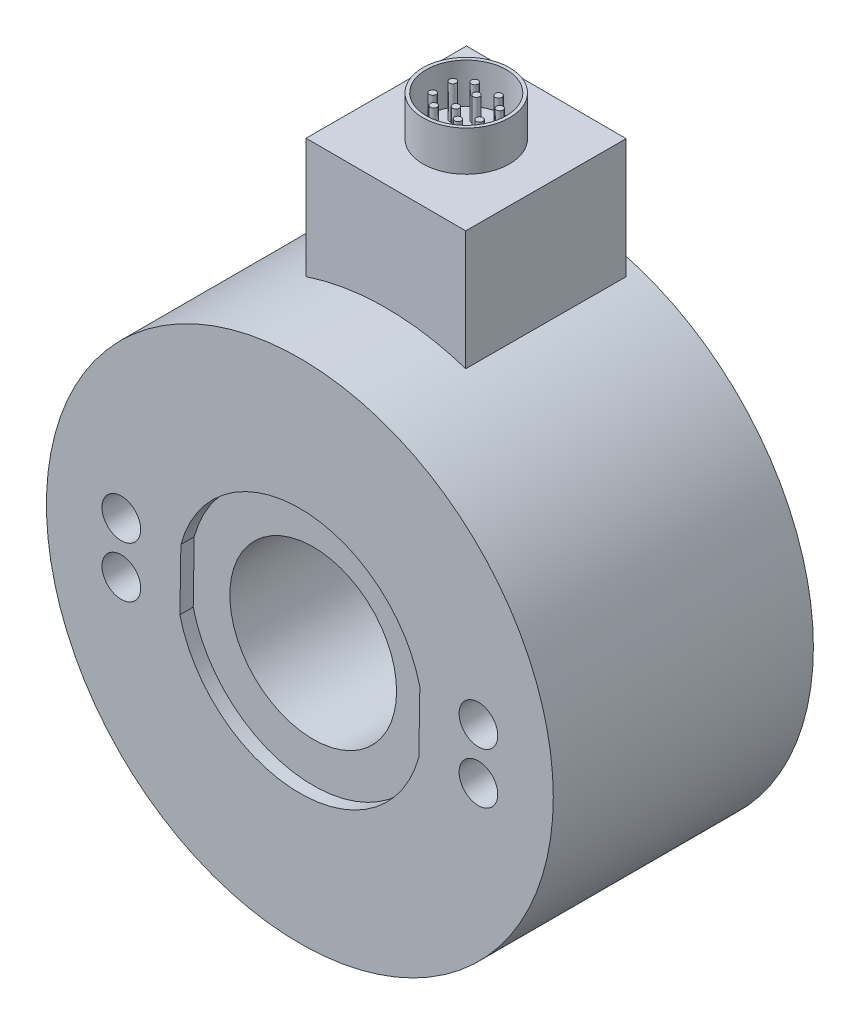
SolidWorks part; units mm, degrees
ref_plane "Спереди" through (0, 0, 0) normal (0, 0, 1) x (1, 0, 0)
ref_plane "Сверху" through (0, 0, 0) normal (0, 1, 0) x (1, 0, 0)
ref_plane "Справа" through (0, 0, 0) normal (1, 0, 0) x (0, 0, -1)
sketch "Эскиз1" plane through (0, 0, 0) normal (0, 0, 1) x (1, 0, 0)
  circle A0 centre (0, 0) radius 38
  dimension "D1" = 76
extrude "Бобышка-Вытянуть1" add sketch "Эскиз1" along normal blind 39
sketch "Эскиз3" plane through (0, 0, 39) normal (0, 0, 1) x (1, 0, 0)
  circle A0 centre (0, 0) radius 17.5
extrude "Бобышка-Вытянуть2" add sketch "Эскиз3" along normal blind 7
sketch "Эскиз5" plane through (0, 0, 46) normal (0, 0, 1) x (1, 0, 0)
  circle A0 centre (0, 0) radius 12
  dimension "D1" = 24
extrude "Вырез-Вытянуть2" cut sketch "Эскиз5" against normal blind 46
chamfer "Фаска2" distance 1 angle 30 1 edges at (12, 0, 46)
sketch "Эскиз6" plane through (0, 0, 0) normal (0, 0, -1) x (-1, 0, 0)
  circle A0 centre (0, 0) radius 12
  circle A2 centre (0, 0) radius 12.5
  dimension "D1" = 24
  dimension "D2" = 25
sketch "Эскиз7" plane through (0, 0, 0) normal (0, 0, -1) x (-1, 0, 0)
  circle A0 centre (0, 0) radius 12.5
  circle A1 centre (0, 0) radius 17
  circle A2 centre (0, 0) radius 16.5
  circle A3 centre (0, 0) radius 13
  circle A4 centre (0, 0) radius 16
  dimension "D1" = 34
  dimension "D2" = 25
  dimension "D3" = 33
  dimension "D4" = 32
  dimension "D5" = 26
extrude "Бобышка-Вытянуть4" add sketch "Эскиз6" along normal blind 1
extrude "Вырез-Вытянуть5" cut sketch "Эскиз7" against normal blind 2 contours A4 A3
fillet "Скругление5" radius 1 1 edges at (-16, 0, 0)
sketch "Эскиз8" plane through (0, 0, 39) normal (0, 0, 1) x (1, 0, 0)
  line L0 (17.9893, 4.3169) -> (17.8406, -4.8952)
  line L2 (-17.9893, -4.3169) -> (-17.8406, 4.8952)
  circle A0 centre (0, 0) radius 22.5
  arc A1 (17.9893, 4.3169) -> (-17.8406, 4.8952) centre (0, 0) ccw
  arc A2 (-17.9893, -4.3169) -> (17.8406, -4.8952) centre (0, 0) ccw
extrude "Вырез-Вытянуть12" cut sketch "Эскиз8" against normal blind 2 contours L0 A2 L2 A1
sketch "Эскиз10" plane through (0, 0, 0) normal (0, 1, 0) x (1, 0, 0)
  line L2 (-12.1049, -25.9702) -> (11.8951, -26.0284)
  line L3 (-12.1049, -25.9702) -> (-12.0467, -1.9703)
  line L4 (-12.0467, -1.9703) -> (11.9532, -2.0284)
  line L5 (11.8951, -26.0284) -> (11.9532, -2.0284)
  dimension "D1" = 24
  dimension "D2" = 24
  dimension "D3" = 11.9532
  dimension "D4" = 25.9702
  dimension "D5" = 1.9995
extrude "Бобышка-Вытянуть7" add sketch "Эскиз10" along normal blind 24 from offset 30
sketch "Эскиз16" plane through (0, 54, 0) normal (0, 1, 0) x (1, 0, 0)
  line L2 (-7.9939, -24.0871) -> (8.0849, -24.0871)
  line L3 (-9.9939, -22.0871) -> (-9.9939, -6.0476)
  line L4 (-7.9939, -4.0476) -> (8.0849, -4.0476)
  line L5 (10.0849, -22.0871) -> (10.0849, -6.0476)
  arc A0 (-7.9939, -4.0476) -> (-9.9939, -6.0476) centre (-7.9939, -6.0476) ccw
  arc A1 (10.0849, -6.0476) -> (8.0849, -4.0476) centre (8.0849, -6.0476) ccw
  arc A2 (8.0849, -24.0871) -> (10.0849, -22.0871) centre (8.0849, -22.0871) ccw
  arc A3 (-9.9939, -22.0871) -> (-7.9939, -24.0871) centre (-7.9939, -22.0871) ccw
  circle A4 centre (0, -14.0522) radius 6.5
  circle A5 centre (0, -14.0522) radius 6
  dimension "D1" = 2
  dimension "D2" = 2
  dimension "D3" = 2
  dimension "D4" = 13
  dimension "D5" = 12
extrude "Бобышка-Вытянуть9" add sketch "Эскиз16" along normal blind 6
sketch "Эскиз17" plane through (0, 54, 0) normal (0, 1, 0) x (1, 0, 0)
  circle A0 centre (-3.5122, -12.553) radius 0.5
  circle A1 centre (0.0201, -12.5388) radius 0.5
  circle A2 centre (3.5086, -12.5388) radius 0.5
  circle A3 centre (3.472, -15.5271) radius 0.5
  circle A4 centre (-0.0165, -15.5881) radius 0.5
  circle A5 centre (-3.5293, -15.5515) radius 0.5
  circle A6 centre (-1.7464, -11.0326) radius 0.5
  circle A7 centre (1.7682, -10.975) radius 0.5
  circle A8 centre (1.7826, -17.0823) radius 0.5
  circle A9 centre (-1.804, -17.1255) radius 0.5
extrude "Бобышка-Вытянуть10" add sketch "Эскиз17" along normal blind 5
sketch "Эскиз18" plane through (0, 0, -1) normal (0, 0, -1) x (-1, 0, 0)
  circle A0 centre (0, 0) radius 12.5
extrude "Вырез-Вытянуть13" cut sketch "Эскиз18" against normal through all
sketch "Эскиз19" plane through (0, 0, 46) normal (0, 0, 1) x (1, 0, 0)
  circle A0 centre (0, 0) radius 17.5
extrude "Вырез-Вытянуть14" cut sketch "Эскиз19" against normal blind 7
sketch "Эскиз20" plane through (0, 0, 39) normal (0, 0, 1) x (1, 0, 0)
  line L0 (-26.7726, -3.8139) -> (26.7726, 3.8139) construction
  line L5 (-26.7726, 3.8139) -> (26.7726, -3.8139) construction
  point P0 (0, 0)
hole_wizard "Отверстие с зазором M51" positions "Трехмерный эскиз2" profile "Эскиз22" hole size "M5" standard "ISO"
sketch3d "Трехмерный эскиз2"
  point P0 (-26.7726, 3.8139, 39)
  point P3 (-26.7726, -3.8139, 39)
  point P6 (26.7726, 3.8139, 39)
  point P9 (26.7726, -3.8139, 39)
sketch "Эскиз22" plane through (-26.7726, 3.8139, 39) normal (1, 0, 0) x (0, -1, 0)
  line L0 (0, 0) -> (0, 15.7425)
  line L1 (0, 15.7425) -> (2.9, 14)
  line L2 (2.9, 14) -> (2.9, 0)
  line L5 (2.9, 0) -> (0, 0)
  line L10 (0, 15.7425) -> (-2.9, 14) construction
  line L11 (0, -6.35) -> (0, 107.95) construction
  dimension "Диаметр отверстия" = 5.8
  dimension "Глубина отверстия" = 14
  dimension "Угол заточки сверла" = 118
